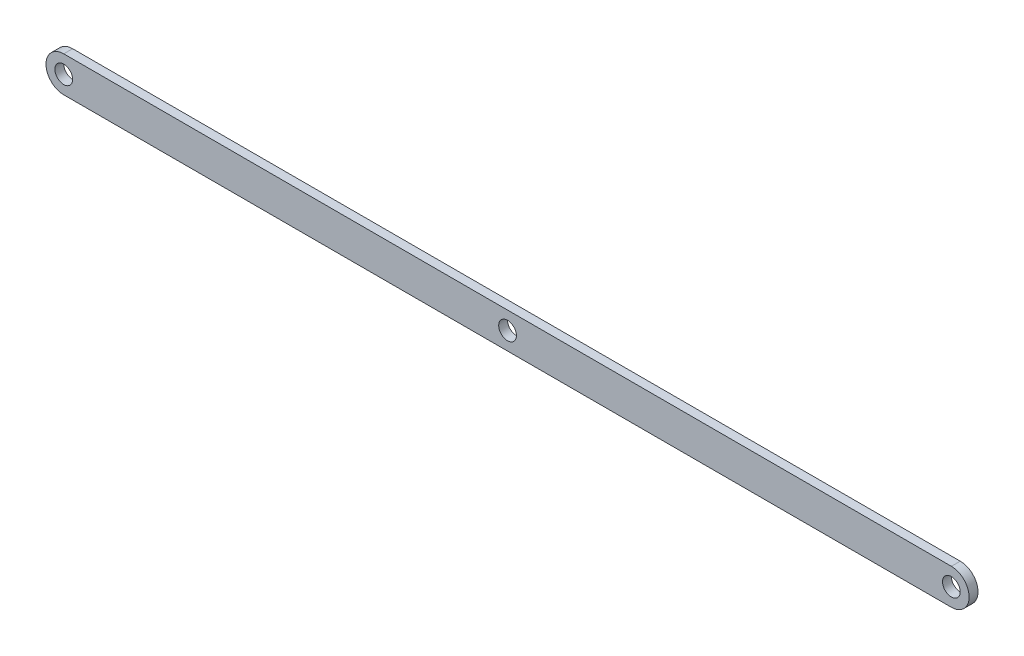
SolidWorks part; units mm, degrees
ref_plane "Front Plane" through (0, 0, 0) normal (0, 0, 1) x (1, 0, 0)
ref_plane "Top Plane" through (0, 0, 0) normal (0, 1, 0) x (1, 0, 0)
ref_plane "Right Plane" through (0, 0, 0) normal (1, 0, 0) x (0, 0, -1)
sketch "Sketch1" plane through (0, 0, 0) normal (0, 0, 1) x (1, 0, 0)
  line L0 (-250, 0) -> (250, 0) construction
  line L1 (-250, 10) -> (250, 10)
  line L2 (-250, -10) -> (250, -10)
  arc A0 (-250, 10) -> (-250, -10) centre (-250, 0) ccw
  arc A1 (250, -10) -> (250, 10) centre (250, 0) ccw
  circle A2 centre (-250, 0) radius 5
  circle A3 centre (0, 0) radius 5
  circle A4 centre (250, 0) radius 5
  point P2 (0, 0)
  dimension "D3" = 10
  dimension "D1" = 500
  dimension "D2" = 20
  dimension "D4" = 3
extrude "Boss-Extrude1" add sketch "Sketch1" along normal blind 5
